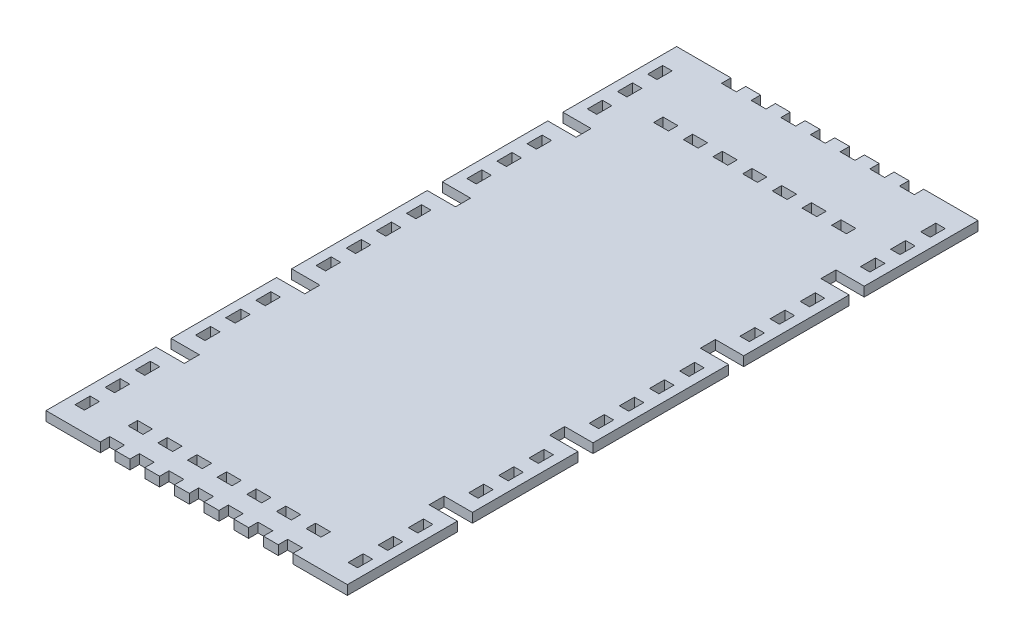
SolidWorks part; units mm, degrees
ref_plane "Front Plane" through (0, 0, 0) normal (0, 0, 1) x (1, 0, 0)
ref_plane "Top Plane" through (0, 0, 0) normal (0, 1, 0) x (1, 0, 0)
ref_plane "Right Plane" through (0, 0, 0) normal (1, 0, 0) x (0, 0, -1)
sketch "Sketch2" plane through (0, 0, 0) normal (0, 1, 0) x (1, 0, 0)
  line L0 (-14.0992, -170.1134) -> (-14.0992, 42.4846) construction
  line L1 (-64.8992, -170.1134) -> (-46.5992, -170.1134)
  line L2 (-64.8992, -170.1134) -> (-64.8992, -133.0294)
  line L3 (-64.8992, 42.4846) -> (-46.5992, 42.4846)
  line L4 (36.7008, -170.1134) -> (36.7008, -133.0294)
  line L5 (-61.7242, -163.5094) -> (-58.5492, -163.5094)
  line L6 (-61.7242, -163.5094) -> (-61.7242, -158.4294)
  line L7 (-61.7242, -158.4294) -> (-58.5492, -158.4294)
  line L8 (-58.5492, -163.5094) -> (-58.5492, -158.4294)
  line L9 (30.3508, -163.5094) -> (30.3508, -158.4294)
  line L10 (33.5258, -158.4294) -> (30.3508, -158.4294)
  line L11 (33.5258, -163.5094) -> (33.5258, -158.4294)
  line L12 (33.5258, -163.5094) -> (30.3508, -163.5094)
  line L13 (-61.7242, -153.3494) -> (-58.5492, -153.3494)
  line L14 (-61.7242, -153.3494) -> (-61.7242, -148.2694)
  line L15 (-61.7242, -148.2694) -> (-58.5492, -148.2694)
  line L16 (-58.5492, -153.3494) -> (-58.5492, -148.2694)
  line L17 (-61.7242, -143.1894) -> (-58.5492, -143.1894)
  line L18 (-61.7242, -143.1894) -> (-61.7242, -138.1094)
  line L19 (-61.7242, -138.1094) -> (-58.5492, -138.1094)
  line L20 (-58.5492, -143.1894) -> (-58.5492, -138.1094)
  line L22 (-64.8992, -87.3094) -> (-64.8992, -41.5894)
  line L23 (36.7008, -127.9494) -> (27.1758, -127.9494)
  line L24 (-64.8992, -36.5094) -> (-64.8992, -0.9494)
  line L25 (-61.7242, -122.8694) -> (-58.5492, -122.8694)
  line L26 (-61.7242, -122.8694) -> (-61.7242, -117.7894)
  line L27 (-61.7242, -117.7894) -> (-58.5492, -117.7894)
  line L28 (-58.5492, -122.8694) -> (-58.5492, -117.7894)
  line L29 (-61.7242, -112.7094) -> (-58.5492, -112.7094)
  line L30 (-61.7242, -112.7094) -> (-61.7242, -107.6294)
  line L31 (-61.7242, -107.6294) -> (-58.5492, -107.6294)
  line L32 (-58.5492, -112.7094) -> (-58.5492, -107.6294)
  line L33 (-61.7242, -102.5494) -> (-58.5492, -102.5494)
  line L34 (-61.7242, -102.5494) -> (-61.7242, -97.4694)
  line L35 (-61.7242, -97.4694) -> (-58.5492, -97.4694)
  line L36 (-58.5492, -102.5494) -> (-58.5492, -97.4694)
  line L38 (-64.8992, 4.1306) -> (-64.8992, 42.4846)
  line L39 (36.7008, -133.0294) -> (27.1758, -133.0294)
  line L40 (27.1758, -127.9494) -> (27.1758, -133.0294)
  line L41 (-61.7242, -82.2294) -> (-58.5492, -82.2294)
  line L42 (-61.7242, -82.2294) -> (-61.7242, -77.1494)
  line L43 (-61.7242, -77.1494) -> (-58.5492, -77.1494)
  line L44 (-58.5492, -82.2294) -> (-58.5492, -77.1494)
  line L45 (-61.7242, -72.0694) -> (-58.5492, -72.0694)
  line L46 (-61.7242, -72.0694) -> (-61.7242, -66.9894)
  line L47 (-61.7242, -66.9894) -> (-58.5492, -66.9894)
  line L48 (-58.5492, -72.0694) -> (-58.5492, -66.9894)
  line L49 (-61.7242, -61.9094) -> (-58.5492, -61.9094)
  line L50 (-61.7242, -61.9094) -> (-61.7242, -56.8294)
  line L51 (-61.7242, -56.8294) -> (-58.5492, -56.8294)
  line L52 (-58.5492, -61.9094) -> (-58.5492, -56.8294)
  line L53 (-61.7242, -51.7494) -> (-58.5492, -51.7494)
  line L54 (-61.7242, -51.7494) -> (-61.7242, -46.6694)
  line L55 (-61.7242, -46.6694) -> (-58.5492, -46.6694)
  line L56 (-58.5492, -51.7494) -> (-58.5492, -46.6694)
  line L61 (-61.7242, -31.4294) -> (-58.5492, -31.4294)
  line L62 (-61.7242, -31.4294) -> (-61.7242, -26.3494)
  line L63 (-61.7242, -26.3494) -> (-58.5492, -26.3494)
  line L64 (-58.5492, -31.4294) -> (-58.5492, -26.3494)
  line L65 (-61.7242, -21.2694) -> (-58.5492, -21.2694)
  line L66 (-61.7242, -21.2694) -> (-61.7242, -16.1894)
  line L67 (-61.7242, -16.1894) -> (-58.5492, -16.1894)
  line L68 (-58.5492, -21.2694) -> (-58.5492, -16.1894)
  line L69 (-61.7242, -11.1094) -> (-58.5492, -11.1094)
  line L70 (-61.7242, -11.1094) -> (-61.7242, -6.0294)
  line L71 (-61.7242, -6.0294) -> (-58.5492, -6.0294)
  line L72 (-58.5492, -11.1094) -> (-58.5492, -6.0294)
  line L77 (-61.7242, 9.2106) -> (-58.5492, 9.2106)
  line L78 (-61.7242, 9.2106) -> (-61.7242, 14.2906)
  line L79 (-61.7242, 14.2906) -> (-58.5492, 14.2906)
  line L80 (-58.5492, 9.2106) -> (-58.5492, 14.2906)
  line L81 (-61.7242, 19.3706) -> (-58.5492, 19.3706)
  line L82 (-61.7242, 19.3706) -> (-61.7242, 24.4506)
  line L83 (-61.7242, 24.4506) -> (-58.5492, 24.4506)
  line L84 (-58.5492, 19.3706) -> (-58.5492, 24.4506)
  line L85 (-61.7242, 29.5306) -> (-58.5492, 29.5306)
  line L86 (-61.7242, 29.5306) -> (-61.7242, 34.6106)
  line L87 (-61.7242, 34.6106) -> (-58.5492, 34.6106)
  line L88 (-58.5492, 29.5306) -> (-58.5492, 34.6106)
  line L89 (30.3508, 29.5306) -> (30.3508, 34.6106)
  line L90 (33.5258, 34.6106) -> (30.3508, 34.6106)
  line L91 (33.5258, 29.5306) -> (33.5258, 34.6106)
  line L92 (33.5258, 29.5306) -> (30.3508, 29.5306)
  line L93 (30.3508, 19.3706) -> (30.3508, 24.4506)
  line L94 (33.5258, 24.4506) -> (30.3508, 24.4506)
  line L95 (33.5258, 19.3706) -> (33.5258, 24.4506)
  line L96 (33.5258, 19.3706) -> (30.3508, 19.3706)
  line L97 (30.3508, 9.2106) -> (30.3508, 14.2906)
  line L98 (33.5258, 14.2906) -> (30.3508, 14.2906)
  line L99 (33.5258, 9.2106) -> (33.5258, 14.2906)
  line L100 (33.5258, 9.2106) -> (30.3508, 9.2106)
  line L101 (36.7008, -36.5094) -> (36.7008, -0.9494)
  line L103 (27.1758, -41.5894) -> (36.7008, -41.5894)
  line L105 (30.3508, -11.1094) -> (30.3508, -6.0294)
  line L106 (33.5258, -6.0294) -> (30.3508, -6.0294)
  line L107 (33.5258, -11.1094) -> (33.5258, -6.0294)
  line L108 (33.5258, -11.1094) -> (30.3508, -11.1094)
  line L109 (30.3508, -21.2694) -> (30.3508, -16.1894)
  line L110 (33.5258, -16.1894) -> (30.3508, -16.1894)
  line L111 (33.5258, -21.2694) -> (33.5258, -16.1894)
  line L112 (33.5258, -21.2694) -> (30.3508, -21.2694)
  line L113 (30.3508, -31.4294) -> (30.3508, -26.3494)
  line L114 (33.5258, -26.3494) -> (30.3508, -26.3494)
  line L115 (33.5258, -31.4294) -> (33.5258, -26.3494)
  line L116 (33.5258, -31.4294) -> (30.3508, -31.4294)
  line L117 (36.7008, -87.3094) -> (36.7008, -41.5894)
  line L119 (27.1758, -92.3894) -> (36.7008, -92.3894)
  line L121 (30.3508, -51.7494) -> (30.3508, -46.6694)
  line L122 (33.5258, -46.6694) -> (30.3508, -46.6694)
  line L123 (33.5258, -51.7494) -> (33.5258, -46.6694)
  line L124 (33.5258, -51.7494) -> (30.3508, -51.7494)
  line L125 (30.3508, -61.9094) -> (30.3508, -56.8294)
  line L126 (33.5258, -56.8294) -> (30.3508, -56.8294)
  line L127 (33.5258, -61.9094) -> (33.5258, -56.8294)
  line L128 (33.5258, -61.9094) -> (30.3508, -61.9094)
  line L129 (30.3508, -72.0694) -> (30.3508, -66.9894)
  line L130 (33.5258, -66.9894) -> (30.3508, -66.9894)
  line L131 (33.5258, -72.0694) -> (33.5258, -66.9894)
  line L132 (33.5258, -72.0694) -> (30.3508, -72.0694)
  line L133 (30.3508, -82.2294) -> (30.3508, -77.1494)
  line L134 (33.5258, -77.1494) -> (30.3508, -77.1494)
  line L135 (33.5258, -82.2294) -> (33.5258, -77.1494)
  line L136 (33.5258, -82.2294) -> (30.3508, -82.2294)
  line L137 (-64.8992, -127.9494) -> (-64.8992, -92.3894)
  line L139 (-55.3742, -127.9494) -> (-64.8992, -127.9494)
  line L141 (30.3508, -102.5494) -> (30.3508, -97.4694)
  line L142 (33.5258, -97.4694) -> (30.3508, -97.4694)
  line L143 (33.5258, -102.5494) -> (33.5258, -97.4694)
  line L144 (33.5258, -102.5494) -> (30.3508, -102.5494)
  line L145 (30.3508, -112.7094) -> (30.3508, -107.6294)
  line L146 (33.5258, -107.6294) -> (30.3508, -107.6294)
  line L147 (33.5258, -112.7094) -> (33.5258, -107.6294)
  line L148 (33.5258, -112.7094) -> (30.3508, -112.7094)
  line L149 (30.3508, -122.8694) -> (30.3508, -117.7894)
  line L150 (33.5258, -117.7894) -> (30.3508, -117.7894)
  line L151 (33.5258, -122.8694) -> (33.5258, -117.7894)
  line L152 (33.5258, -122.8694) -> (30.3508, -122.8694)
  line L153 (36.7008, 4.1306) -> (36.7008, 42.4846)
  line L155 (27.1758, -0.9494) -> (36.7008, -0.9494)
  line L157 (30.3508, -143.1894) -> (30.3508, -138.1094)
  line L158 (33.5258, -138.1094) -> (30.3508, -138.1094)
  line L159 (33.5258, -143.1894) -> (33.5258, -138.1094)
  line L160 (33.5258, -143.1894) -> (30.3508, -143.1894)
  line L161 (30.3508, -153.3494) -> (30.3508, -148.2694)
  line L162 (33.5258, -148.2694) -> (30.3508, -148.2694)
  line L163 (33.5258, -153.3494) -> (33.5258, -148.2694)
  line L164 (33.5258, -153.3494) -> (30.3508, -153.3494)
  line L165 (-46.5992, 42.4846) -> (-46.5992, 39.3096)
  line L166 (-46.5992, 39.3096) -> (-41.5992, 39.3096)
  line L167 (-41.5992, 39.3096) -> (-41.5992, 42.4846)
  line L168 (-36.5992, 42.4846) -> (-36.5992, 39.3096)
  line L169 (-36.5992, 39.3096) -> (-31.5992, 39.3096)
  line L170 (-31.5992, 39.3096) -> (-31.5992, 42.4846)
  line L171 (-26.5992, 42.4846) -> (-26.5992, 39.3096)
  line L172 (-26.5992, 39.3096) -> (-21.5992, 39.3096)
  line L173 (-21.5992, 39.3096) -> (-21.5992, 42.4846)
  line L174 (-16.5992, 42.4846) -> (-16.5992, 39.3096)
  line L175 (-16.5992, 39.3096) -> (-11.5992, 39.3096)
  line L176 (-11.5992, 39.3096) -> (-11.5992, 42.4846)
  line L177 (-6.5992, 42.4846) -> (-6.5992, 39.3096)
  line L178 (-6.5992, 39.3096) -> (-1.5992, 39.3096)
  line L179 (-1.5992, 39.3096) -> (-1.5992, 42.4846)
  line L180 (3.4008, 42.4846) -> (3.4008, 39.3096)
  line L181 (3.4008, 39.3096) -> (8.4008, 39.3096)
  line L182 (8.4008, 39.3096) -> (8.4008, 42.4846)
  line L183 (13.4008, 42.4846) -> (13.4008, 39.3096)
  line L184 (13.4008, 39.3096) -> (18.4008, 39.3096)
  line L185 (18.4008, 39.3096) -> (18.4008, 42.4846)
  line L186 (-41.5992, 42.4846) -> (-36.5992, 42.4846) construction
  line L187 (-41.5992, 42.4846) -> (-36.5992, 42.4846)
  line L188 (-21.5992, 42.4846) -> (-16.5992, 42.4846)
  line L189 (-31.5992, 42.4846) -> (-26.5992, 42.4846)
  line L190 (-11.5992, 42.4846) -> (-6.5992, 42.4846)
  line L191 (-1.5992, 42.4846) -> (3.4008, 42.4846)
  line L192 (8.4008, 42.4846) -> (13.4008, 42.4846)
  line L193 (18.4008, 42.4846) -> (36.7008, 42.4846)
  line L194 (-46.5992, 19.6106) -> (-46.5992, 16.4356)
  line L195 (-46.5992, 16.4356) -> (-41.5992, 16.4356)
  line L196 (-41.5992, 16.4356) -> (-41.5992, 19.6106)
  line L197 (-36.5992, 19.6106) -> (-36.5992, 16.4356)
  line L198 (-36.5992, 16.4356) -> (-31.5992, 16.4356)
  line L199 (-31.5992, 16.4356) -> (-31.5992, 19.6106)
  line L200 (-26.5992, 19.6106) -> (-26.5992, 16.4356)
  line L201 (-26.5992, 16.4356) -> (-21.5992, 16.4356)
  line L202 (-21.5992, 16.4356) -> (-21.5992, 19.6106)
  line L203 (-16.5992, 19.6106) -> (-16.5992, 16.4356)
  line L204 (-16.5992, 16.4356) -> (-11.5992, 16.4356)
  line L205 (-11.5992, 16.4356) -> (-11.5992, 19.6106)
  line L206 (-6.5992, 19.6106) -> (-6.5992, 16.4356)
  line L207 (-6.5992, 16.4356) -> (-1.5992, 16.4356)
  line L208 (-1.5992, 16.4356) -> (-1.5992, 19.6106)
  line L209 (3.4008, 19.6106) -> (3.4008, 16.4356)
  line L210 (3.4008, 16.4356) -> (8.4008, 16.4356)
  line L211 (8.4008, 16.4356) -> (8.4008, 19.6106)
  line L212 (13.4008, 19.6106) -> (13.4008, 16.4356)
  line L213 (13.4008, 16.4356) -> (18.4008, 16.4356)
  line L214 (18.4008, 16.4356) -> (18.4008, 19.6106)
  line L215 (-46.5992, 19.6106) -> (-41.5992, 19.6106)
  line L216 (-36.5992, 19.6106) -> (-31.5992, 19.6106)
  line L217 (-26.5992, 19.6106) -> (-21.5992, 19.6106)
  line L218 (-16.5992, 19.6106) -> (-11.5992, 19.6106)
  line L219 (-6.5992, 19.6106) -> (-1.5992, 19.6106)
  line L220 (3.4008, 19.6106) -> (8.4008, 19.6106)
  line L221 (13.4008, 19.6106) -> (18.4008, 19.6106)
  line L222 (-41.5992, 19.6106) -> (-36.5992, 19.6106) [skipped]
  line L223 (-41.5992, 19.6106) -> (-36.5992, 19.6106) construction
  line L224 (-31.5992, 19.6106) -> (-26.5992, 19.6106) [skipped]
  line L225 (-21.5992, 19.6106) -> (-16.5992, 19.6106) [skipped]
  line L226 (-11.5992, 19.6106) -> (-6.5992, 19.6106) [skipped]
  line L227 (-1.5992, 19.6106) -> (3.4008, 19.6106) [skipped]
  line L228 (8.4008, 19.6106) -> (13.4008, 19.6106) [skipped]
  line L229 (-64.8992, -63.8144) -> (36.7008, -63.8144) construction
  line L230 (-41.5992, -170.1134) -> (-36.5992, -170.1134)
  line L231 (13.4008, -160.7154) -> (18.4008, -160.7154)
  line L232 (3.4008, -160.7154) -> (8.4008, -160.7154)
  line L233 (-6.5992, -160.7154) -> (-1.5992, -160.7154)
  line L234 (-16.5992, -160.7154) -> (-11.5992, -160.7154)
  line L235 (-26.5992, -160.7154) -> (-21.5992, -160.7154)
  line L236 (-36.5992, -160.7154) -> (-31.5992, -160.7154)
  line L237 (-46.5992, -160.7154) -> (-41.5992, -160.7154)
  line L238 (18.4008, -157.5404) -> (18.4008, -160.7154)
  line L239 (13.4008, -157.5404) -> (18.4008, -157.5404)
  line L240 (13.4008, -160.7154) -> (13.4008, -157.5404)
  line L241 (8.4008, -157.5404) -> (8.4008, -160.7154)
  line L242 (3.4008, -157.5404) -> (8.4008, -157.5404)
  line L243 (3.4008, -160.7154) -> (3.4008, -157.5404)
  line L244 (-1.5992, -157.5404) -> (-1.5992, -160.7154)
  line L245 (-6.5992, -157.5404) -> (-1.5992, -157.5404)
  line L246 (-6.5992, -160.7154) -> (-6.5992, -157.5404)
  line L247 (-11.5992, -157.5404) -> (-11.5992, -160.7154)
  line L248 (-16.5992, -157.5404) -> (-11.5992, -157.5404)
  line L249 (-16.5992, -160.7154) -> (-16.5992, -157.5404)
  line L250 (-21.5992, -157.5404) -> (-21.5992, -160.7154)
  line L251 (-26.5992, -157.5404) -> (-21.5992, -157.5404)
  line L252 (-26.5992, -160.7154) -> (-26.5992, -157.5404)
  line L253 (-31.5992, -157.5404) -> (-31.5992, -160.7154)
  line L254 (-36.5992, -157.5404) -> (-31.5992, -157.5404)
  line L255 (-36.5992, -160.7154) -> (-36.5992, -157.5404)
  line L256 (-41.5992, -157.5404) -> (-41.5992, -160.7154)
  line L257 (-46.5992, -157.5404) -> (-41.5992, -157.5404)
  line L258 (-46.5992, -160.7154) -> (-46.5992, -157.5404)
  line L259 (-31.5992, -170.1134) -> (-26.5992, -170.1134)
  line L260 (-21.5992, -170.1134) -> (-16.5992, -170.1134)
  line L261 (-11.5992, -170.1134) -> (-6.5992, -170.1134)
  line L262 (-1.5992, -170.1134) -> (3.4008, -170.1134)
  line L263 (8.4008, -170.1134) -> (13.4008, -170.1134)
  line L265 (18.4008, -170.1134) -> (18.4008, -166.9384)
  line L266 (13.4008, -166.9384) -> (18.4008, -166.9384)
  line L267 (13.4008, -170.1134) -> (13.4008, -166.9384)
  line L268 (8.4008, -170.1134) -> (8.4008, -166.9384)
  line L269 (3.4008, -166.9384) -> (8.4008, -166.9384)
  line L270 (3.4008, -170.1134) -> (3.4008, -166.9384)
  line L271 (-1.5992, -170.1134) -> (-1.5992, -166.9384)
  line L272 (-6.5992, -166.9384) -> (-1.5992, -166.9384)
  line L273 (-6.5992, -170.1134) -> (-6.5992, -166.9384)
  line L274 (-11.5992, -170.1134) -> (-11.5992, -166.9384)
  line L275 (-16.5992, -166.9384) -> (-11.5992, -166.9384)
  line L276 (-16.5992, -170.1134) -> (-16.5992, -166.9384)
  line L277 (-21.5992, -170.1134) -> (-21.5992, -166.9384)
  line L278 (-26.5992, -166.9384) -> (-21.5992, -166.9384)
  line L279 (-26.5992, -170.1134) -> (-26.5992, -166.9384)
  line L280 (-31.5992, -170.1134) -> (-31.5992, -166.9384)
  line L281 (-36.5992, -166.9384) -> (-31.5992, -166.9384)
  line L282 (-36.5992, -170.1134) -> (-36.5992, -166.9384)
  line L283 (-41.5992, -170.1134) -> (-41.5992, -166.9384)
  line L284 (-46.5992, -166.9384) -> (-41.5992, -166.9384)
  line L285 (-46.5992, -170.1134) -> (-46.5992, -166.9384)
  line L290 (36.7008, -127.9494) -> (36.7008, -92.3894)
  line L291 (18.4008, -170.1134) -> (36.7008, -170.1134)
  line L292 (27.1758, -0.9494) -> (27.1758, 4.1306)
  line L293 (27.1758, 4.1306) -> (36.7008, 4.1306)
  line L294 (27.1758, -41.5894) -> (27.1758, -36.5094)
  line L295 (27.1758, -36.5094) -> (36.7008, -36.5094)
  line L296 (27.1758, -92.3894) -> (27.1758, -87.3094)
  line L297 (27.1758, -87.3094) -> (36.7008, -87.3094)
  line L298 (-55.3742, -127.9494) -> (-55.3742, -133.0294)
  line L299 (-55.3742, -133.0294) -> (-64.8992, -133.0294)
  line L301 (-55.3742, -87.3094) -> (-64.8992, -87.3094)
  line L302 (-55.3742, -87.3094) -> (-55.3742, -92.3894)
  line L303 (-55.3742, -92.3894) -> (-64.8992, -92.3894)
  line L305 (-55.3742, -36.5094) -> (-64.8992, -36.5094)
  line L306 (-55.3742, -36.5094) -> (-55.3742, -41.5894)
  line L307 (-55.3742, -41.5894) -> (-64.8992, -41.5894)
  line L309 (-55.3742, 4.1306) -> (-64.8992, 4.1306)
  line L310 (-55.3742, 4.1306) -> (-55.3742, -0.9494)
  line L311 (-55.3742, -0.9494) -> (-64.8992, -0.9494)
  line L313 (-58.5492, -133.0294) -> (-58.5492, -127.9494) [skipped]
  line L314 (-61.7242, -133.0294) -> (-61.7242, -127.9494) [skipped]
  line L315 (-58.5492, -92.3894) -> (-58.5492, -87.3094) [skipped]
  line L316 (-61.7242, -92.3894) -> (-61.7242, -87.3094) [skipped]
  line L317 (-58.5492, -41.5894) -> (-58.5492, -36.5094) [skipped]
  line L318 (-61.7242, -41.5894) -> (-61.7242, -36.5094) [skipped]
  line L319 (-58.5492, -0.9494) -> (-58.5492, 4.1306) [skipped]
  line L320 (-61.7242, -0.9494) -> (-61.7242, 4.1306) [skipped]
  line L321 (-61.7242, -133.0294) -> (-58.5492, -133.0294) [skipped]
  line L322 (-61.7242, -127.9494) -> (-58.5492, -127.9494) [skipped]
  line L323 (-61.7242, -92.3894) -> (-58.5492, -92.3894) [skipped]
  line L324 (-61.7242, -87.3094) -> (-58.5492, -87.3094) [skipped]
  line L325 (-61.7242, -41.5894) -> (-58.5492, -41.5894) [skipped]
  line L326 (-61.7242, -36.5094) -> (-58.5492, -36.5094) [skipped]
  line L327 (-61.7242, -0.9494) -> (-58.5492, -0.9494) [skipped]
  line L328 (-61.7242, 4.1306) -> (-58.5492, 4.1306) [skipped]
  dimension "D1" = 101.6
  dimension "D2" = 198.12
  dimension "D3" = 3.175
  dimension "D4" = 3.175
  dimension "D5" = 5.08
  dimension "D6" = 3.175
  dimension "D8" = 6.604
  dimension "D9" = 5
  dimension "D10" = 10
  dimension "D11" = 2
  dimension "D12" = 7
  dimension "D13" = 19.699
  dimension "D14" = 9.525
  dimension "D15" = 9.525
  dimension "D16" = 9.525
  dimension "D17" = 9.525
  dimension "D18" = 9.525
  dimension "D19" = 9.525
  dimension "D20" = 9.525
  dimension "D21" = 9.525
  dimension "D7" = 20
extrude "Boss-Extrude1" add sketch "Sketch2" along normal blind 3.175
sketch "Sketch3" plane through (0, 0, 0) normal (0, -1, 0) x (-1, 0, 0)
